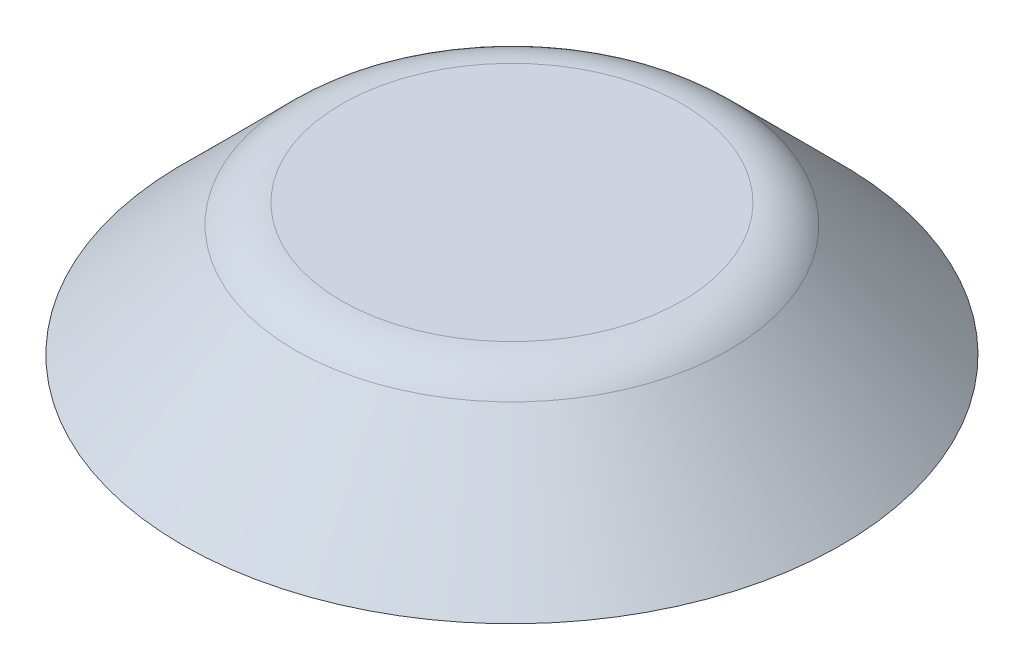
SolidWorks part; units mm, degrees
ref_plane "Front Plane" through (0, 0, 0) normal (0, 0, 1) x (1, 0, 0)
ref_plane "Top Plane" through (0, 0, 0) normal (0, 1, 0) x (1, 0, 0)
ref_plane "Right Plane" through (0, 0, 0) normal (1, 0, 0) x (0, 0, -1)
sketch "Sketch1" plane through (0, 0, 0) normal (0, 1, 0) x (1, 0, 0)
  circle A0 centre (0, 0) radius 12.5
  dimension "D1" = 25
extrude "Boss-Extrude1" add sketch "Sketch1" along normal blind 5 draft 45
sketch "Sketch2" plane through (0, 0, 0) normal (0, -1, 0) x (1, 0, 0)
  circle A0 centre (0, 0) radius 5
  dimension "D1" = 10
fillet "Fillet2" radius 2.5 1 edges at (0, 5, 7.5)
extrude "Cut-Extrude1" cut sketch "Sketch2" against normal blind 3 contours A0
